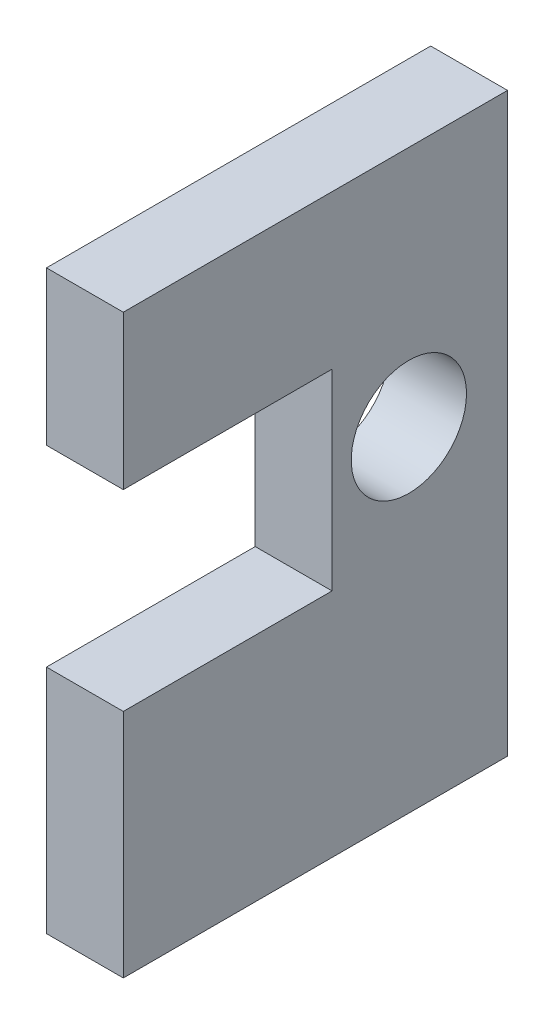
SolidWorks part; units mm, degrees
ref_plane "Front Plane" through (0, 0, 0) normal (0, 0, 1) x (1, 0, 0)
ref_plane "Top Plane" through (0, 0, 0) normal (0, 1, 0) x (1, 0, 0)
ref_plane "Right Plane" through (0, 0, 0) normal (1, 0, 0) x (0, 0, -1)
sketch "Sketch1" plane through (0, 0, 0) normal (1, 0, 0) x (0, 0, -1)
  line L0 (0.4324, -6.9715) -> (-5, -6.9715)
  line L1 (5, -12.9799) -> (-5, -12.9799)
  line L2 (5, -12.9799) -> (5, 2.027)
  line L4 (-5, -12.9799) -> (-5, -6.9715)
  line L6 (-5, -1.973) -> (-5, 2.027)
  line L7 (0.4324, -6.9715) -> (0.4324, -1.973)
  line L8 (0.4324, -1.973) -> (-5, -1.973)
  line L12 (5, 2.027) -> (-5, 2.027)
  circle A0 centre (2.4324, -4.273) radius 1.5
  point P0 (0, 0)
  point P8 (-3.0665, -4.4722)
  dimension "D1" = 10
  dimension "D3" = 2.3
extrude "Boss-Extrude1" add sketch "Sketch1" along normal blind 2
